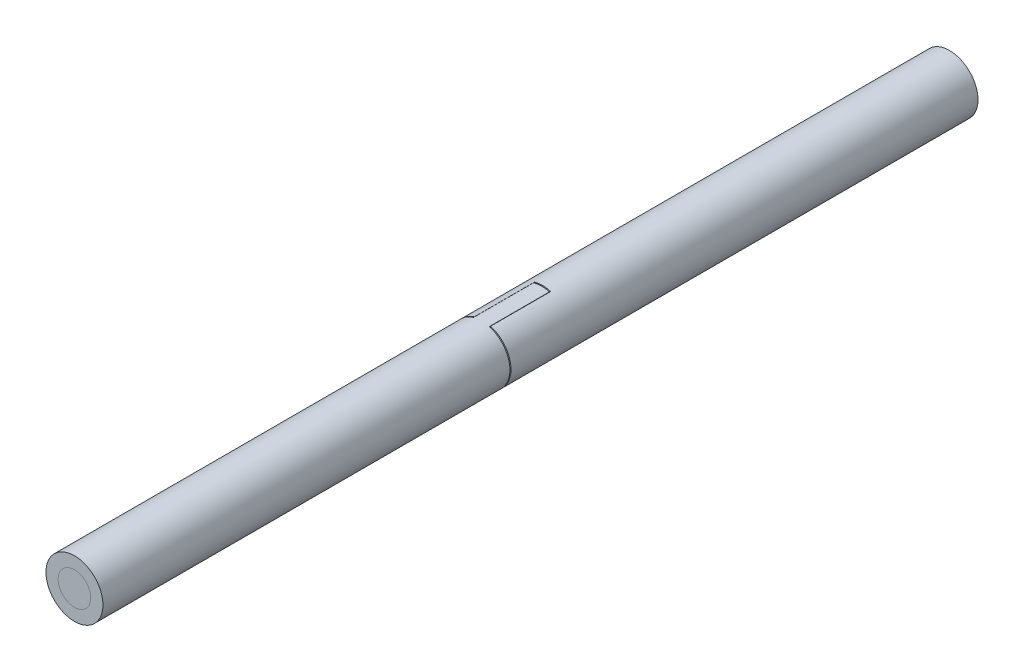
SolidWorks part; units mm, degrees
ref_plane "Front Plane" through (0, 0, 0) normal (0, 0, 1) x (1, 0, 0)
ref_plane "Top Plane" through (0, 0, 0) normal (0, 1, 0) x (1, 0, 0)
ref_plane "Right Plane" through (0, 0, 0) normal (1, 0, 0) x (0, 0, -1)
ref_plane "Plane1" through (0, 0, 7.5) normal (0, 0, 1) x (1, 0, 0)
ref_plane "Plane2" through (0, 0, -7.5) normal (0, 0, 1) x (1, 0, 0)
sketch "Sketch1" plane through (0, 0, -7.5) normal (0, 0, 1) x (1, 0, 0)
  circle A0 centre (0, 0) radius 7
  circle A1 centre (0, 0) radius 4
  dimension "D1" = 14
  dimension "D2" = 8
extrude "Boss-Extrude1" add sketch "Sketch1" against normal blind 100
sketch "Sketch2" plane through (0, 0, 7.5) normal (0, 0, 1) x (1, 0, 0)
  circle A0 centre (0, 0) radius 4 construction
  circle A1 centre (0, 0) radius 7
  circle A2 centre (0, 0) radius 7
  circle A3 centre (0, 0) radius 4
  dimension "D1" = 0
extrude "Boss-Extrude2" add sketch "Sketch2" along normal blind 100 separate body
sketch "Sketch3" plane through (0, 0, -7.5) normal (0, 0, 1) x (1, 0, 0)
  circle A0 centre (0, 0) radius 4 construction
  circle A1 centre (0, 0) radius 7
  circle A2 centre (0, 0) radius 7
  circle A3 centre (0, 0) radius 4
  dimension "D1" = 0
extrude "Boss-Extrude3" add sketch "Sketch3" along normal blind 14.75
sketch "Sketch4" plane through (0, 0, -7.5) normal (0, 0, 1) x (1, 0, 0)
  line L0 (-2, -6.7082) -> (-2, 6.7082)
  line L1 (2, -6.7082) -> (2, 6.7082)
  circle A0 centre (0, 0) radius 7 construction
  circle A1 centre (0, 0) radius 7
  arc A2 (2, 6.7082) -> (-2, 6.7082) centre (0, 0) ccw
  arc A3 (2, -6.7082) -> (2, 6.7082) centre (0, 0) ccw construction
  arc A4 (-2, 6.7082) -> (-2, -6.7082) centre (0, 0) ccw construction
  arc A5 (-2, -6.7082) -> (2, -6.7082) centre (0, 0) ccw
  dimension "D1" = 2
  dimension "D2" = 2
extrude "Cut-Extrude1" cut sketch "Sketch4" along normal up to surface (15 mm away) up to plane "Plane1"
sketch "Sketch5" plane through (0, 0, 7.5) normal (0, 0, 1) x (1, 0, 0)
  line L0 (1.95, 6.7229) -> (1.95, 3.4925)
  line L1 (-1.95, 6.7229) -> (-1.95, 3.4925)
  line L2 (1.95, 3.4925) -> (1.95, -3.4925) construction
  line L3 (1.95, -3.4925) -> (1.95, -6.7229)
  line L4 (-1.95, 3.4925) -> (-1.95, -3.4925) construction
  line L5 (-1.95, -3.4925) -> (-1.95, -6.7229)
  circle A0 centre (0, 0) radius 7 construction
  arc A1 (1.95, 6.7229) -> (-1.95, 6.7229) centre (0, 0) ccw
  arc A2 (1.95, -6.7229) -> (1.95, 6.7229) centre (0, 0) ccw construction
  arc A3 (-1.95, 6.7229) -> (-1.95, -6.7229) centre (0, 0) ccw construction
  arc A4 (-1.95, -6.7229) -> (1.95, -6.7229) centre (0, 0) ccw
  circle A5 centre (0, 0) radius 4 construction
  arc A6 (-1.95, -3.4925) -> (1.95, -3.4925) centre (0, 0) ccw
  arc A7 (-1.95, 3.4925) -> (-1.95, -3.4925) centre (0, 0) ccw construction
  arc A8 (1.95, -3.4925) -> (1.95, 3.4925) centre (0, 0) ccw construction
  arc A9 (1.95, 3.4925) -> (-1.95, 3.4925) centre (0, 0) ccw
  dimension "D1" = 1.95
  dimension "D2" = 1.95
extrude "Boss-Extrude4" add sketch "Sketch5" against normal blind 14.75
sketch "Sketch6" plane through (0, 0, -7.5) normal (0, 0, 1) x (1, 0, 0)
  circle A0 centre (0, 0) radius 4
  dimension "D1" = 8
extrude "Boss-Extrude5" add sketch "Sketch6" against normal blind 100 separate body
sketch "Sketch7" plane through (0, 0, 7.5) normal (0, 0, 1) x (1, 0, 0)
  circle A1 centre (0, 0) radius 4
  circle A2 centre (0, 0) radius 4
  dimension "D1" = 0
extrude "Boss-Extrude6" add sketch "Sketch7" along normal blind 100 separate body
sketch "Sketch8" plane through (0, 0, 7.5) normal (0, 0, 1) x (1, 0, 0)
  line L0 (2, 3.4641) -> (2, -3.4641)
  line L1 (-2, -3.4641) -> (-2, 3.4641)
  circle A0 centre (0, 0) radius 4 construction
  arc A1 (-2, 3.4641) -> (-2, -3.4641) centre (0, 0) ccw
  arc A2 (2, 3.4641) -> (-2, 3.4641) centre (0, 0) ccw construction
  arc A3 (-2, -3.4641) -> (2, -3.4641) centre (0, 0) ccw construction
  arc A4 (2, -3.4641) -> (2, 3.4641) centre (0, 0) ccw
  dimension "D1" = 2
  dimension "D2" = 2
extrude "Boss-Extrude7" add sketch "Sketch8" against normal blind 14.75
sketch "Sketch9" plane through (0, 0, -7.5) normal (0, 0, 1) x (1, 0, 0)
  line L0 (-1.95, 3.4925) -> (-1.95, -3.4925)
  line L1 (1.95, 3.4925) -> (1.95, -3.4925)
  circle A0 centre (0, 0) radius 4 construction
  arc A1 (1.95, 3.4925) -> (-1.95, 3.4925) centre (0, 0) ccw
  arc A2 (1.95, -3.4925) -> (1.95, 3.4925) centre (0, 0) ccw construction
  arc A3 (-1.95, 3.4925) -> (-1.95, -3.4925) centre (0, 0) ccw construction
  arc A4 (-1.95, -3.4925) -> (1.95, -3.4925) centre (0, 0) ccw
  point P7 (0.9358, -3.86)
  dimension "D1" = 1.95
  dimension "D2" = 1.95
extrude "Boss-Extrude8" add sketch "Sketch9" along normal blind 14.75
